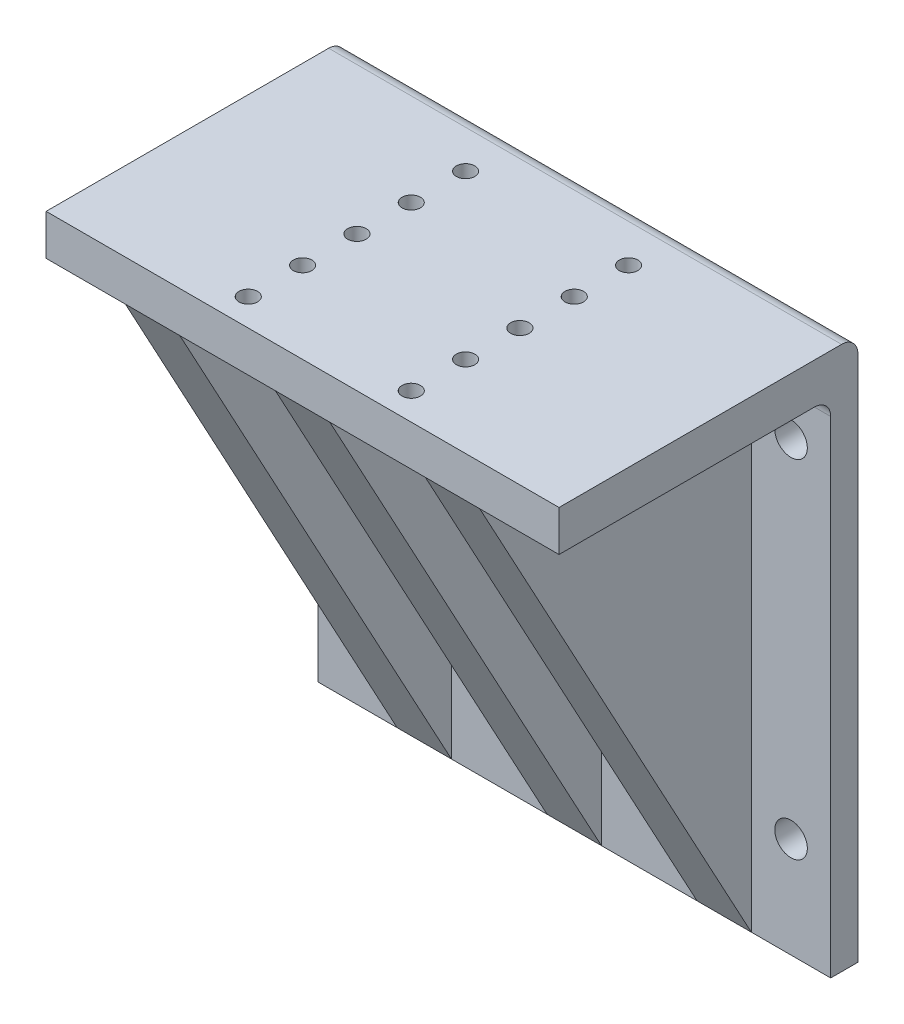
SolidWorks part; units mm, degrees
ref_plane "Front Plane" through (0, 0, 0) normal (0, 0, 1) x (1, 0, 0)
ref_plane "Top Plane" through (0, 0, 0) normal (0, 1, 0) x (1, 0, 0)
ref_plane "Right Plane" through (0, 0, 0) normal (1, 0, 0) x (0, 0, -1)
sketch "Sketch1" plane through (0, 0, 0) normal (0, 0, 1) x (1, 0, 0)
  line L0 (94.4, 100) -> (0, 100)
  line L1 (0, 0) -> (92, 0)
  line L2 (0, 0) -> (0, 100)
  line L3 (0, 100) -> (92, 100)
  line L4 (92, 0) -> (92, 100)
  line L5 (92, 100) -> (94.4, 100)
  line L6 (92, 100) -> (92, 0)
  line L7 (92, 0) -> (94.4, 0)
  line L8 (94.4, 100) -> (94.4, 0)
  line L9 (47.2, 100) -> (47.2, 0) construction
  line L10 (94.4, 50) -> (0, 50) construction
  circle A8 centre (7.3, 66.66) radius 3
  circle A9 centre (87.1, 82.32) radius 3
  circle A10 centre (87.1, 18.5) radius 3
  circle A11 centre (7.3, 20.94) radius 3
  dimension "D1" = 92
  dimension "D2" = 100
  dimension "D10" = 2.4
extrude "Boss-Extrude1" add sketch "Sketch1" along normal blind 5
sketch "Sketch2" plane through (0, 0, 5) normal (0, 0, 1) x (1, 0, 0)
  line L0 (94.4, 100) -> (94.4, 0) construction
  line L1 (0, 100) -> (94.4, 100)
  line L2 (0, 100) -> (0, 92.5)
  line L3 (0, 92.5) -> (94.4, 92.5)
  line L4 (94.4, 100) -> (94.4, 92.5)
  dimension "D1" = 7.5
extrude "Boss-Extrude2" add sketch "Sketch2" along normal blind 50
ref_plane "Plane1" through (47.2, 0, 0) normal (1, 0, 0) x (0, 0, -1)
sketch "Sketch7" plane through (47.2, 0, 0) normal (1, 0, 0) x (0, 0, -1)
  line L0 (-55, 92.5) -> (-5, 0)
  line L1 (-5, 0) -> (0, 0) construction
  line L4 (-55, 92.5) -> (-5, 92.5)
  line L5 (-5, 92.5) -> (-5, 0)
  point P5 (0, 0)
extrude "Boss-Extrude3" add sketch "Sketch7" along normal blind 5 and the other way blind 5
pattern_linear "LPattern1" count 2 spacing 27.6 along (-1, 0, 0) count 2 spacing 27.6 along (1, 0, 0) of "Boss-Extrude3"
fillet "Fillet1" radius 3 5 edges at (47.2, 100, 0) (7.3, 92.5, 5) (61, 92.5, 5) (87.1, 92.5, 5) (33.4, 92.5, 5)
sketch "Sketch9" plane through (0, 92.5, 0) normal (0, -1, 0) x (1, 0, 0)
  line L0 (47.2, 55) -> (47.2, 5) construction
  line L3 (42.2, 55) -> (52.2, 55) construction
  line L4 (42.2, 5) -> (52.2, 5) construction
  line L5 (24.6, 55) -> (42.2, 55) construction
  circle A0 centre (32.2, 50) radius 1.7
  circle A2 centre (62.2, 50) radius 1.7
  circle A3 centre (62.2, 40) radius 1.7
  circle A4 centre (62.2, 30) radius 1.7
  circle A5 centre (62.2, 20) radius 1.7
  circle A6 centre (62.2, 10) radius 1.7
  circle A7 centre (32.2, 40) radius 1.7
  circle A8 centre (32.2, 30) radius 1.7
  circle A9 centre (32.2, 20) radius 1.7
  circle A10 centre (32.2, 10) radius 1.7
  dimension "D1" = 3.4
  dimension "D4" = 5
  dimension "D3" = 15
  dimension "D5" = 2
  dimension "D6" = 5
extrude "Cut-Extrude2" cut sketch "Sketch9" against normal up to next
